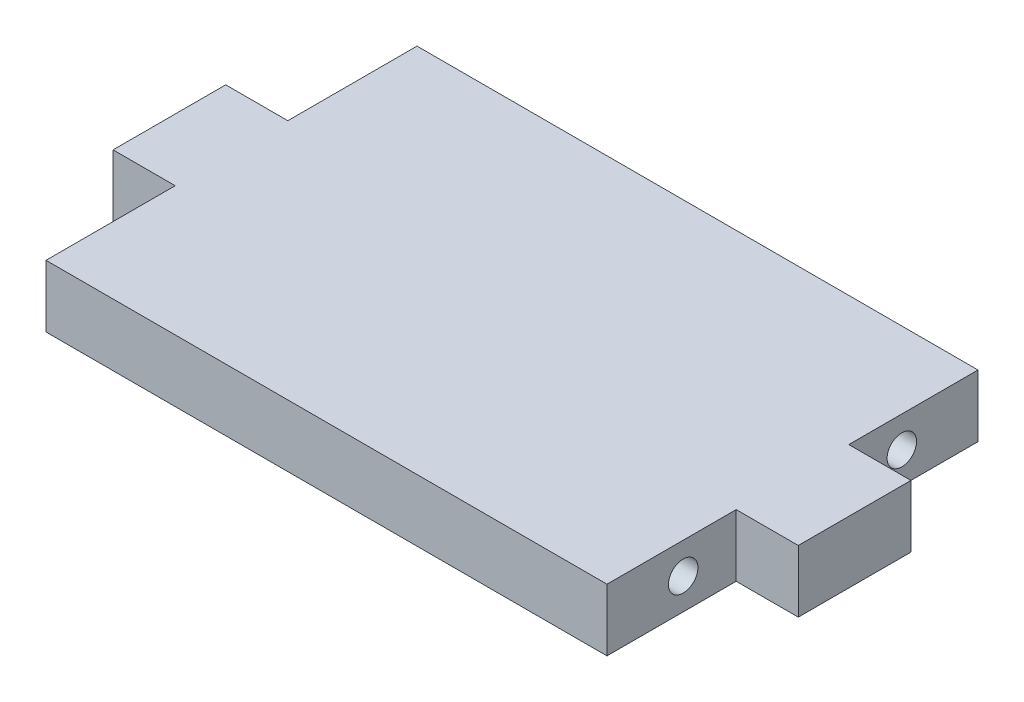
SolidWorks part; units mm, degrees
ref_plane "Front Plane" through (0, 0, 0) normal (0, 0, 1) x (1, 0, 0)
ref_plane "Top Plane" through (0, 0, 0) normal (0, 1, 0) x (1, 0, 0)
ref_plane "Right Plane" through (0, 0, 0) normal (1, 0, 0) x (0, 0, -1)
sketch "Sketch3" plane through (0, 0, 0) normal (0, 1, 0) x (1, 0, 0)
  line L0 (-21.5075, 14.224) -> (21.5075, 14.224)
  line L1 (21.5075, 14.224) -> (21.5074, 4.318)
  line L2 (21.5074, 4.318) -> (26.27, 4.318)
  line L3 (26.27, 4.318) -> (26.27, -4.318)
  line L4 (-21.5075, 14.224) -> (-21.5074, 4.318)
  line L5 (-21.5074, 4.318) -> (-26.27, 4.318)
  line L6 (-26.27, 4.318) -> (-26.27, -4.318)
  line L7 (-26.27, 0) -> (26.27, 0) construction
  line L8 (21.5074, -4.318) -> (26.27, -4.318)
  line L9 (21.5075, -14.224) -> (21.5074, -4.318)
  line L10 (-21.5075, -14.224) -> (21.5075, -14.224)
  line L11 (-21.5075, -14.224) -> (-21.5074, -4.318)
  line L12 (-21.5074, -4.318) -> (-26.27, -4.318)
  point P8 (0, 0)
  dimension "D1" = 14.224
  dimension "D2" = 4.7625
  dimension "D3" = 4.318
  dimension "D4" = 43.0149
extrude "Boss-Extrude1" add sketch "Sketch3" along normal blind 4.7625
sketch "Sketch4" plane through (21.5074, 0, 0) normal (1, 0, 0) x (0, 0, -1)
  line L0 (-14.224, 4.7625) -> (-14.224, 0) construction
  circle A0 centre (-8.382, 2.3813) radius 1.1303
  circle A1 centre (8.382, 2.3813) radius 1.1303
  point P6 (-14.224, 2.3813)
  dimension "D3" = 2.2606
  dimension "D1" = 5.842
  dimension "D2" = 16.764
extrude "Cut-Extrude1" cut sketch "Sketch4" against normal through all
